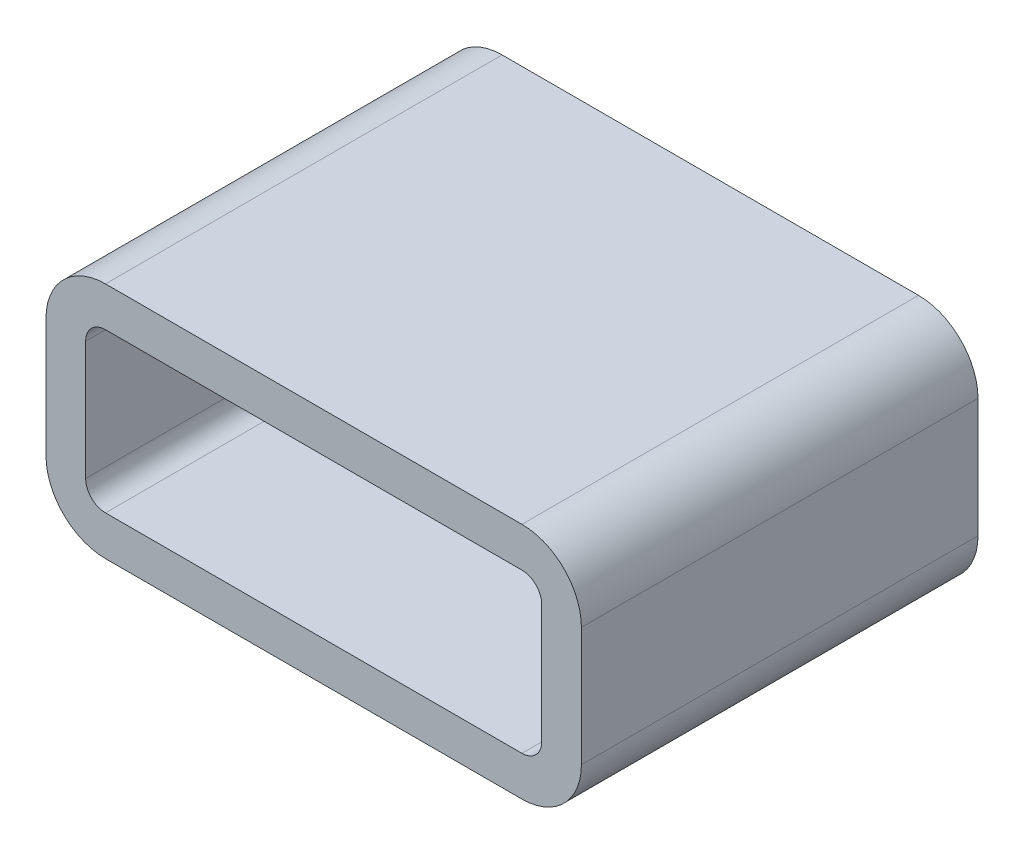
SolidWorks part; units mm, degrees
ref_plane "Alzado" through (0, 0, 0) normal (0, 0, 1) x (1, 0, 0)
ref_plane "Planta" through (0, 0, 0) normal (0, 1, 0) x (1, 0, 0)
ref_plane "Vista lateral" through (0, 0, 0) normal (1, 0, 0) x (0, 0, -1)
sketch "Croquis1" plane through (0, 0, 0) normal (0, 0, 1) x (1, 0, 0)
  line L0 (-13.5, -6) -> (13.5, 6) construction
  line L1 (-13.5, 6) -> (13.5, 6)
  line L2 (-13.5, 6) -> (-13.5, -6)
  line L3 (-13.5, -6) -> (13.5, -6)
  line L4 (13.5, 6) -> (13.5, -6)
  point P4 (0, 0)
  point P5 (-13.5, 13.5668)
  dimension "D1" = 27
  dimension "D2" = 12
extrude "Saliente-Extruir1" add sketch "Croquis1" along normal blind 20 contours L2 L3 L4 L1
sketch "Croquis2" plane through (0, 0, 20) normal (0, 0, 1) x (1, 0, 0)
  line L12 (11.5, 4) -> (-11.5, 4)
  line L13 (-11.5, 4) -> (-11.5, -4)
  line L14 (-11.5, -4) -> (11.5, -4)
  line L15 (11.5, -4) -> (11.5, 4)
  line L16 (11.5, 4) -> (-11.5, 4)
  line L17 (-11.5, 4) -> (-11.5, -4)
  line L18 (-11.5, -4) -> (11.5, -4)
  line L19 (11.5, -4) -> (11.5, 4)
  dimension "D1" = 2
extrude "Cortar-Extruir1" cut sketch "Croquis2" against normal blind 20
fillet "Redondeo1" radius 3 4 edges at (-13.5, 6, 10) (13.5, 6, 10) (13.5, -6, 10) (-13.5, -6, 10)
fillet "Redondeo2" radius 1 4 edges at (11.5, 4, 10) (11.5, -4, 10) (-11.5, -4, 10) (-11.5, 4, 10)
